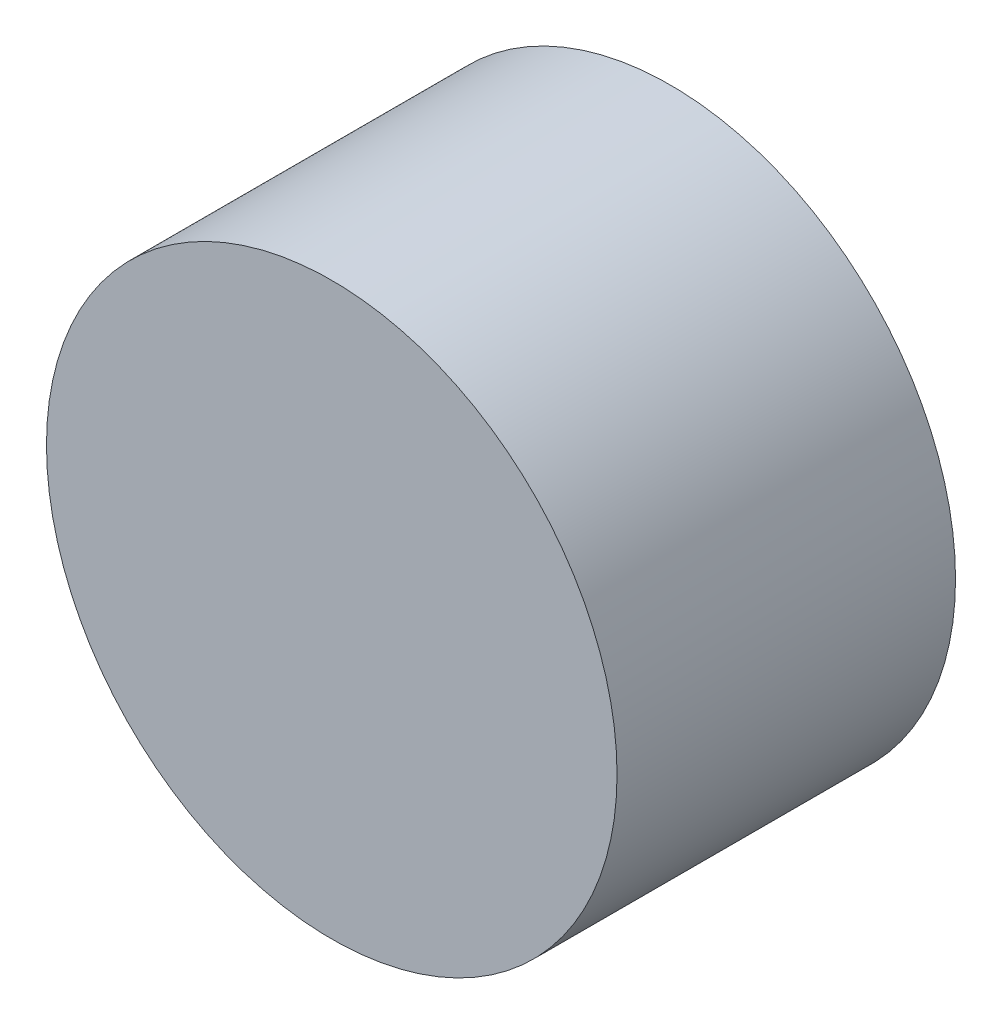
SolidWorks part; units mm, degrees
ref_plane "Front Plane" through (0, 0, 0) normal (0, 0, 1) x (1, 0, 0)
ref_plane "Top Plane" through (0, 0, 0) normal (0, 1, 0) x (1, 0, 0)
ref_plane "Right Plane" through (0, 0, 0) normal (1, 0, 0) x (0, 0, -1)
sketch "Sketch1" plane through (0, 0, 0) normal (0, 0, 1) x (1, 0, 0)
  circle A0 centre (0, 0) radius 2.95
  dimension "D1" = 5.9
extrude "Boss-Extrude1" add sketch "Sketch1" along normal blind 3.5
